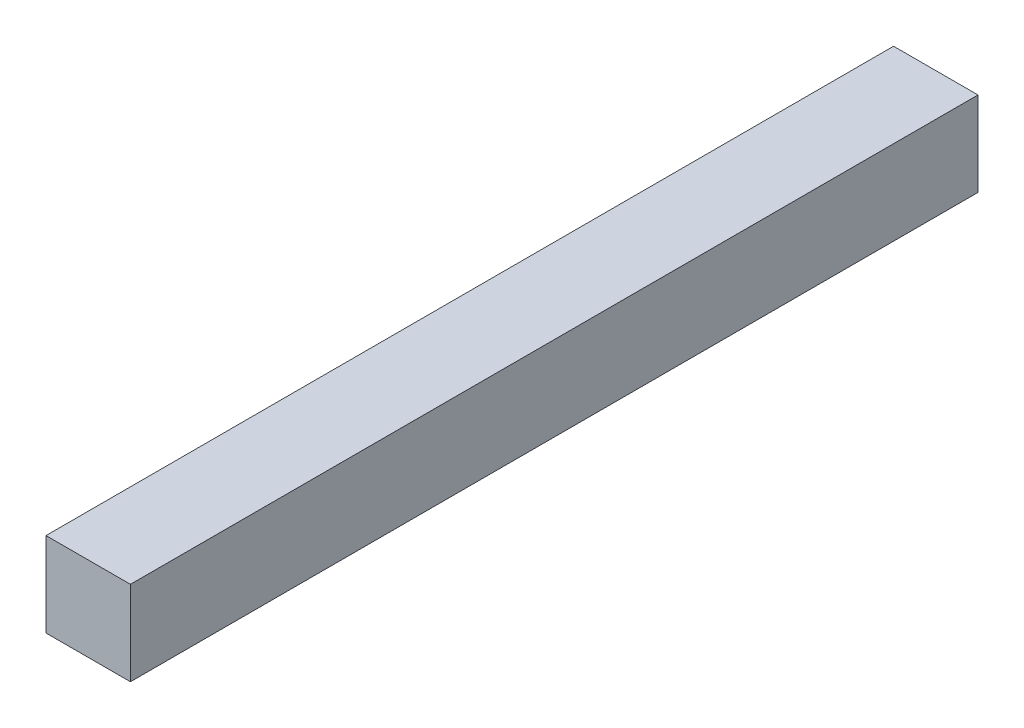
SolidWorks part; units mm, degrees
material "ABS PC"
ref_plane "Front Plane" through (0, 0, 0) normal (0, 0, 1) x (1, 0, 0)
ref_plane "Top Plane" through (0, 0, 0) normal (0, 1, 0) x (1, 0, 0)
ref_plane "Right Plane" through (0, 0, 0) normal (1, 0, 0) x (0, 0, -1)
sketch "Sketch1" plane through (0, 0, 35.7224) normal (0, 0, 1) x (1, 0, 0)
  line L1 (-22.7496, 59.4567) -> (-30.3696, 59.4567)
  line L2 (-22.7496, 59.4567) -> (-22.7496, 51.8367)
  line L3 (-22.7496, 51.8367) -> (-30.3696, 51.8367)
  line L4 (-30.3696, 59.4567) -> (-30.3696, 51.8367)
  dimension "D1" = 7.62
extrude "Boss-Extrude1" add sketch "Sketch1" along normal up to vertex (76.5048 mm away)
